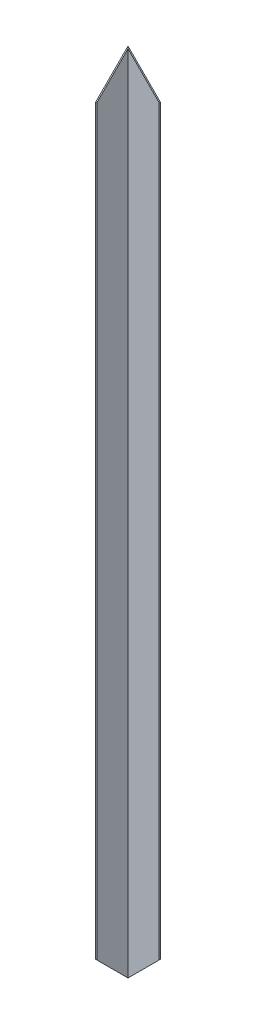
SolidWorks part; units mm, degrees
material "1060 Legierung"
ref_plane "Ebene vorne" through (0, 0, 0) normal (0, 0, 1) x (1, 0, 0)
ref_plane "Ebene oben" through (0, 0, 0) normal (0, 1, 0) x (1, 0, 0)
ref_plane "Ebene rechts" through (0, 0, 0) normal (1, 0, 0) x (0, 0, -1)
sketch "Skizze1" plane through (0, 0, 0) normal (0, 1, 0) x (1, 0, 0)
  line L0 (-461.5, 4) -> (-461.5, 5.5)
  line L1 (-500, 4) -> (500, 4) construction
  line L2 (-461.5, 5.5) -> (-501.5, 5.5)
  line L3 (-501.5, 5.5) -> (-501.5, -34.5)
  line L4 (-501.5, -34.5) -> (-500, -34.5)
  line L5 (-500, -300) -> (-500, 0) construction
  line L6 (-500, -34.5) -> (-500, 4)
  line L7 (-500, 4) -> (-461.5, 4)
  dimension "D1" = 1.5
  dimension "D2" = 40
extrude "Aufsatz-Linear austragen1" add sketch "Skizze1" along normal offset from surface 0.1 and the other way offset from surface (499.9 mm away) 0.1
sketch "Skizze2" plane through (0, 0, -5.5) normal (0, 0, -1) x (-1, 0, 0)
  line L0 (501.5, 499.9) -> (461.5, 459.9)
  line L1 (461.5, 499.9) -> (461.5, -499.9) construction
  line L2 (461.5, 459.9) -> (461.5, 499.9)
  line L3 (461.5, 499.9) -> (501.5, 499.9)
  line L4 (461.5, 0) -> (501.5, 0) construction
  line L5 (501.5, 499.9) -> (501.5, -499.9) construction
  line L6 (461.5, -459.9) -> (461.5, -499.9)
  line L7 (501.5, -499.9) -> (461.5, -459.9)
  line L8 (461.5, -499.9) -> (501.5, -499.9)
  dimension "D1" = 45
extrude "Schnitt-Linear austragen1" cut sketch "Skizze2" against normal up to surface (1.5 mm away) up to face at (-480.75, 0, -4)
sketch "Skizze3" plane through (-501.5, 0, 0) normal (-1, 0, 0) x (0, 0, 1)
  line L0 (34.5, 499.9) -> (-5.5, 499.9)
  line L1 (-5.5, 499.9) -> (34.5, 459.9)
  line L2 (34.5, 499.9) -> (34.5, -499.9) construction
  line L3 (34.5, 459.9) -> (34.5, 499.9)
  line L4 (34.5, 0) -> (-5.5, 0) construction
  line L5 (-5.5, 499.9) -> (-5.5, -499.9) construction
  line L6 (-5.5, -499.9) -> (34.5, -459.9)
  line L7 (34.5, -499.9) -> (-5.5, -499.9)
  line L8 (34.5, -459.9) -> (34.5, -499.9)
  dimension "D1" = 45
extrude "Schnitt-Linear austragen2" cut sketch "Skizze3" against normal up to surface (1.5 mm away) up to face at (-500, 0, 8.8333)
